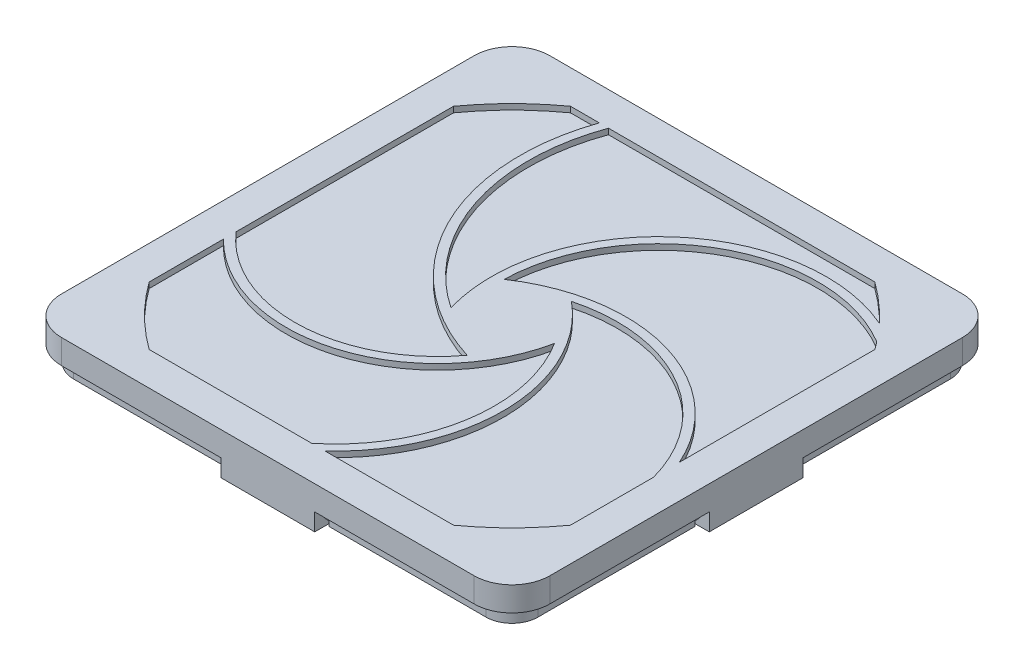
SolidWorks part; units mm, degrees
material "Custom Plastic"
ref_plane "Front" through (0, 0, 0) normal (0, 0, 1) x (1, 0, 0)
ref_plane "Top" through (0, 0, 0) normal (0, 1, 0) x (1, 0, 0)
ref_plane "Right" through (0, 0, 0) normal (1, 0, 0) x (0, 0, -1)
sketch "Sketch2" plane through (0, 0, 0) normal (0, 1, 0) x (1, 0, 0)
  line L1 (-52.4, 62) -> (52.4, 62)
  line L2 (-62, 52.4) -> (-62, -52.4)
  line L3 (-52.4, -62) -> (52.4, -62)
  line L4 (62, 52.4) -> (62, -52.4)
  line L5 (-52.4, 52.4) -> (52.4, 52.4) construction
  line L6 (-52.4, 52.4) -> (-52.4, -52.4) construction
  line L7 (-52.4, -52.4) -> (52.4, -52.4) construction
  line L8 (52.4, 52.4) -> (52.4, -52.4) construction
  arc A0 (-62, -52.4) -> (-52.4, -62) centre (-52.4, -52.4) ccw
  arc A1 (52.4, -62) -> (62, -52.4) centre (52.4, -52.4) ccw
  arc A2 (62, 52.4) -> (52.4, 62) centre (52.4, 52.4) ccw
  arc A3 (-62, 52.4) -> (-52.4, 62) centre (-52.4, 52.4) cw
  circle A4 centre (-52.4, 52.4) radius 2.25 construction
  circle A5 centre (52.4, 52.4) radius 2.25 construction
  circle A6 centre (-52.4, -52.4) radius 2.25 construction
  circle A7 centre (52.4, -52.4) radius 2.25 construction
  point P12 (0, 62)
  point P13 (-62, 0)
  dimension "D2" = 4.5
  dimension "D1" = 124
  dimension "D3" = 104.8
extrude "Boss-Extrude1" add sketch "Sketch2" along normal blind 6.2
ref_plane "Plane1" through (0, 3.1, 0) normal (0, 1, 0) x (-1, 0, 0)
sketch "Sketch11" plane through (0, 0, 0) normal (0, -1, 0) x (1, 0, 0)
  line L8 (-59.4, 52.4) -> (-59.4, -52.4)
  line L9 (-52.4, -59.4) -> (52.4, -59.4)
  line L10 (59.4, -52.4) -> (59.4, 52.4)
  line L11 (52.4, 59.4) -> (-52.4, 59.4)
  line L12 (-59.4, 52.4) -> (-59.4, -52.4)
  line L13 (-52.4, -59.4) -> (52.4, -59.4)
  line L14 (59.4, -52.4) -> (59.4, 52.4)
  line L15 (52.4, 59.4) -> (-52.4, 59.4)
  arc A8 (-52.4, 59.4) -> (-59.4, 52.4) centre (-52.4, 52.4) ccw
  arc A9 (-59.4, -52.4) -> (-52.4, -59.4) centre (-52.4, -52.4) ccw
  arc A10 (52.4, -59.4) -> (59.4, -52.4) centre (52.4, -52.4) ccw
  arc A11 (59.4, 52.4) -> (52.4, 59.4) centre (52.4, 52.4) ccw
  arc A12 (-52.4, 59.4) -> (-59.4, 52.4) centre (-52.4, 52.4) ccw
  arc A13 (-59.4, -52.4) -> (-52.4, -59.4) centre (-52.4, -52.4) ccw
  arc A14 (52.4, -59.4) -> (59.4, -52.4) centre (52.4, -52.4) ccw
  arc A15 (59.4, 52.4) -> (52.4, 59.4) centre (52.4, 52.4) ccw
  dimension "D1" = 2.6
extrude "Cut-Extrude5" cut sketch "Sketch11" against normal offset from surface (4.5 mm away) 1.7 up to face at (0, 6.2, 0)
sketch "Sketch13" plane through (0, 4.5, 0) normal (0, -1, 0) x (1, 0, 0)
  line L8 (-59, 52.4) -> (-59, -52.4)
  line L9 (-52.4, -59) -> (52.4, -59)
  line L10 (59, -52.4) -> (59, 52.4)
  line L11 (52.4, 59) -> (-52.4, 59)
  arc A0 (52.4, -59) -> (59, -52.4) centre (52.4, -52.4) ccw
  circle A1 centre (-52.4, 52.4) radius 2.25 construction
  circle A2 centre (52.4, 52.4) radius 2.25 construction
  circle A3 centre (-52.4, -52.4) radius 2.25 construction
  circle A4 centre (52.4, -52.4) radius 2.25 construction
  circle A5 centre (-52.4, 52.4) radius 2.25
  circle A6 centre (52.4, 52.4) radius 2.25
  circle A7 centre (-52.4, -52.4) radius 2.25
  arc A8 (59, 52.4) -> (52.4, 59) centre (52.4, 52.4) ccw
  arc A9 (-59, 52.4) -> (-52.4, 59) centre (-52.4, 52.4) cw
  arc A10 (-52.4, -59) -> (-59, -52.4) centre (-52.4, -52.4) cw
  circle A12 centre (52.4, -52.4) radius 2.25
  point P3 (-59, 0)
  point P8 (0, 59)
  dimension "D1" = 118
extrude "Boss-Extrude7" add sketch "Sketch13" along normal blind 6.9 from offset 2 separate body
sketch "Sketch17" plane through (0, -4.4, 0) normal (0, -1, 0) x (1, 0, 0)
  line L9 (56, -52.4) -> (56, 52.4)
  line L10 (52.4, 56) -> (-52.4, 56)
  line L11 (-56, 52.4) -> (-56, -52.4)
  line L12 (-52.4, -56) -> (52.4, -56)
  line L13 (56, -47.9164) -> (56, 47.9164)
  line L14 (47.9164, 56) -> (-47.9164, 56)
  line L15 (-56, 47.9164) -> (-56, -47.9164)
  line L16 (-47.9164, -56) -> (47.9164, -56)
  arc A9 (52.4, -56) -> (56, -52.4) centre (52.4, -52.4) ccw
  arc A10 (56, 52.4) -> (52.4, 56) centre (52.4, 52.4) ccw
  arc A11 (-52.4, 56) -> (-56, 52.4) centre (-52.4, 52.4) ccw
  arc A12 (-56, -52.4) -> (-52.4, -56) centre (-52.4, -52.4) ccw
  arc A17 (47.9164, 56) -> (56, 47.9164) centre (52.4, 52.4) ccw
  circle A18 centre (-52.4, 52.4) radius 5.75
  arc A19 (-56, 47.9164) -> (-47.9164, 56) centre (-52.4, 52.4) ccw
  arc A20 (-47.9164, -56) -> (-56, -47.9164) centre (-52.4, -52.4) ccw
  arc A21 (56, -47.9164) -> (47.9164, -56) centre (52.4, -52.4) ccw
  dimension "D2" = 3.5
  dimension "D1" = 3
extrude "Cut-Extrude8" cut sketch "Sketch17" against normal offset from surface (4.88 mm away) 2.02 up to face at (-52.4, 2.5, -54.65)
sketch "Sketch12" plane through (0, 0, 0) normal (0, 0, 1) x (1, 0, 0)
  line L1 (62, -4.4) -> (57.75, -4.4)
  line L2 (57.75, -4.4) -> (59.4, -2.75)
  line L3 (59.4, -2.75) -> (59.4, 0)
  line L4 (59.4, 0) -> (62, 0)
  line L5 (62, -4.4) -> (62, 0)
  dimension "D1" = 10.6
  dimension "D2" = 45
  dimension "D3" = 4.25
extrude "Boss-Extrude6" add sketch "Sketch12" along normal mid plane 23.8
ref_axis "Axis1" through (0, 6.73, 0) along (0, -1, 0)
pattern_circular "CirPattern3" count 4 over 360 about axis through (0, 0, 0) along (0, 1, 0) of "Boss-Extrude6"
sketch "Sketch14" plane through (0, 0, 0) normal (0, 0, 1) x (1, 0, 0)
  line L5 (59.4, 0) -> (59.4, -2.75) construction
  line L6 (62.25, -4.65) -> (62.25, 0.25)
  line L7 (62.25, -4.65) -> (62.25, 0.25)
  line L11 (57.1464, -4.65) -> (62.25, -4.65)
  line L12 (59.15, -2.6464) -> (57.1464, -4.65)
  line L13 (59.15, 0.25) -> (59.15, -2.6464)
  line L14 (62.25, 0.25) -> (59.15, 0.25)
  line L16 (57.1464, -4.65) -> (62.25, -4.65)
  line L17 (59.4, -2.3964) -> (57.1464, -4.65)
  line L18 (59.4, 0.25) -> (59.4, -2.3964)
  line L19 (62.25, 0.25) -> (59.4, 0.25)
  dimension "D1" = 0.25
extrude "Cut-Extrude6" cut sketch "Sketch14" against normal mid plane 25
pattern_circular "CirPattern4" count 4 over 360 about axis through (0, 0, 0) along (0, 1, 0) of "Cut-Extrude6"
sketch "Sketch3" plane through (0, 6.2, 0) normal (0, 1, 0) x (1, 0, 0)
  line L1 (-62, 52.4) -> (-62, -52.4) construction
  line L2 (52.4, 62) -> (-52.4, 62) construction
  line L3 (-52.4, -62) -> (52.4, -62) construction
  line L4 (62, -52.4) -> (62, 52.4) construction
  line L9 (-52.4, -53.5) -> (52.4, -53.5)
  line L14 (53.5, -52.4) -> (53.5, 52.4)
  line L15 (52.4, 53.5) -> (-52.4, 53.5)
  line L16 (-53.5, 52.4) -> (-53.5, -52.4)
  line L17 (-38.6491, -53.5) -> (38.6491, -53.5)
  line L18 (53.5, -38.6491) -> (53.5, 38.6491)
  line L19 (38.6491, 53.5) -> (-38.6491, 53.5)
  line L20 (-53.5, 38.6491) -> (-53.5, -38.6491)
  arc A6 (-38.6491, 53.5) -> (-53.5, 38.6491) centre (0, 0) ccw
  arc A7 (-9.5, -6) -> (-29, 53.5) centre (18.7657, 36.2089) cw
  arc A8 (3, -14.3909) -> (-53.5, -16.5603) centre (-26.1196, 7.1728) cw
  arc A9 (11.5, -0.7) -> (-53.5, -19.8) centre (-26.1196, 7.1728) cw
  arc A10 (9.3466, -0.2494) -> (-51.9327, -18.2561) centre (-26.1196, 7.1728) cw construction
  arc A11 (11.5, -0.7) -> (2.6256, -53.5) centre (-22.7116, -22.0956) cw
  arc A12 (53.5, 38.6491) -> (38.6491, 53.5) centre (0, 0) ccw
  arc A13 (38.6491, -53.5) -> (53.5, -38.6491) centre (0, 0) ccw
  arc A14 (-53.5, -38.6491) -> (-38.6491, -53.5) centre (0, 0) ccw
  arc A15 (-9.5, -6) -> (48.2804, 45) centre (31.3459, 5.9548) cw
  arc A16 (-53.5, -52.4) -> (-52.4, -53.5) centre (-52.4, -52.4) ccw
  arc A17 (52.4, -53.5) -> (53.5, -52.4) centre (52.4, -52.4) ccw
  arc A18 (53.5, 52.4) -> (52.4, 53.5) centre (52.4, 52.4) ccw
  arc A19 (-52.4, 53.5) -> (-53.5, 52.4) centre (-52.4, 52.4) ccw
  arc A20 (-27.179, 18.0074) -> (4.5155, -51.8763) centre (-22.7116, -22.0956) cw construction
  arc A21 (-27.4226, 20.1939) -> (6, -53.5) centre (-22.7116, -22.0956) cw construction
  arc A22 (-13.981, 3.0712) -> (53.5, -11) centre (14.7098, -28.1813) cw construction
  arc A23 (-9, 7) -> (53.5, -11) centre (14.7098, -28.1813) cw
  arc A24 (4.4, 10.7) -> (53.5, -17.5339) centre (14.7098, -28.1813) cw
  arc A25 (4.4, 10.7) -> (6, -53.5) centre (-22.7116, -22.0956) cw
  arc A26 (-12.4932, 1.4505) -> (51.4885, -11.891) centre (14.7098, -28.1813) cw construction
  arc A27 (-9, 7) -> (52.0233, 40.615) centre (31.3459, 5.9548) cw
  arc A28 (-7.3886, -5.382) -> (47.405, 42.9817) centre (31.3459, 5.9548) cw construction
  arc A31 (3, -14.3909) -> (-31.3334, 53.5) centre (18.7657, 36.2089) cw
  point P2 (8.8597, 25.9395)
  point P10 (-15.7592, 44.8536)
  point P11 (-2.9616, -2.7675)
  dimension "D1" = 132
  dimension "D2" = 8.5
  dimension "D3" = 61.3
  dimension "D4" = 52.5
  dimension "D5" = 73.5
  dimension "D13" = 51
  dimension "D22" = 47.6091
  dimension "D7" = 68
  dimension "D10" = 42.2
  dimension "D14" = 56
  dimension "D18" = 2.2
  dimension "D19" = 57.6
  dimension "D12" = 2.2
  dimension "D8" = 33
  dimension "D9" = 17
  dimension "D11" = 2.2
  dimension "D15" = 71
  dimension "D16" = 2.2
  dimension "D17" = 55
  dimension "D20" = 51.3
  dimension "D21" = 65
  dimension "D6" = 2.2
extrude "Cut-Extrude4" cut sketch "Sketch3" against normal through all contours A7 A15 A12 L19 | A8 A31 L19 A6 L20 | A27 A23 L18 A12 | A24 A25 L17 A13 L18 | L20 A14 L17 A11 A9
sketch "Sketch18" plane through (0, 4.5, 0) normal (0, -1, 0) x (1, 0, 0)
  line L0 (-57.9, 47.9) -> (-47.9, 57.9)
  line L1 (-47.9, 57.9) -> (47.9, 57.9)
  line L2 (-57.9, 47.9) -> (-57.9, -47.9)
  line L3 (-47.9, -57.9) -> (47.9, -57.9)
  line L4 (57.9, 47.9) -> (57.9, -47.9)
  line L5 (47.9, 57.9) -> (57.9, 47.9)
  line L6 (57.9, -47.9) -> (47.9, -57.9)
  line L7 (-47.9, -57.9) -> (-57.9, -47.9)
  point P0 (0, 57.9)
  point P2 (-57.9, 0)
  dimension "D1" = 45
  dimension "D2" = 10
  dimension "D3" = 115.8
extrude "Boss-Extrude8" add sketch "Sketch18" along normal blind 3.3 from offset 0.25 separate body offset against normal yes
sketch "Sketch20" plane through (0, 0, 0) normal (1, 0, 0) x (0, 0, -1)
  line L0 (10.7, 2.5) -> (-53.5, 2.5) construction
  line L1 (-59, 2.5) -> (-56.7, 2.5)
  line L2 (-59, 2.5) -> (-59, 0.48)
  line L3 (-59, 0.48) -> (-56.7, 0.48)
  line L4 (-56.7, 2.5) -> (-56.7, 0.48)
  line L5 (-40.74, 2.5) -> (-35.06, 2.5) construction
  line L6 (-56.7, 2.5) -> (-51.02, 2.5) construction
  line L7 (-51.02, 2.5) -> (-48.72, 2.5)
  line L8 (-51.02, 2.5) -> (-51.02, 0.48)
  line L9 (-51.02, 0.48) -> (-48.72, 0.48)
  line L10 (-48.72, 2.5) -> (-48.72, 0.48)
  line L11 (-19.1, 2.5) -> (-16.8, 2.5)
  line L12 (-19.1, 2.5) -> (-19.1, 0.48)
  line L13 (-19.1, 0.48) -> (-16.8, 0.48)
  line L14 (-16.8, 2.5) -> (-16.8, 0.48)
  line L15 (-48.72, 2.5) -> (-43.04, 2.5) construction
  line L18 (-24.78, 2.5) -> (-19.1, 2.5) construction
  line L19 (-35.06, 2.5) -> (-32.76, 2.5)
  line L20 (-43.04, 2.5) -> (-40.74, 2.5)
  line L21 (-27.08, 2.5) -> (-24.78, 2.5)
  line L22 (-27.08, 2.5) -> (-27.08, 0.48)
  line L23 (-27.08, 0.48) -> (-24.78, 0.48)
  line L24 (-24.78, 2.5) -> (-24.78, 0.48)
  line L25 (-43.04, 2.5) -> (-43.04, 0.48)
  line L26 (-43.04, 0.48) -> (-40.74, 0.48)
  line L27 (-40.74, 2.5) -> (-40.74, 0.48)
  line L28 (-35.06, 2.5) -> (-35.06, 0.48)
  line L29 (-35.06, 0.48) -> (-32.76, 0.48)
  line L30 (-32.76, 2.5) -> (-32.76, 0.48)
  line L31 (-32.76, 2.5) -> (-27.08, 2.5) construction
  line L32 (-53.5, 0.48) -> (10.7, 0.48) construction
  dimension "D1" = 2.3
  dimension "D2" = 16.8
  dimension "D3" = 59
revolve "Revolve1" add sketch "Sketch20" angle 360 mid plane about axis through (0, 6.73, 0) along (0, -1, 0)
sketch "Sketch10" plane through (0, 0, 0) normal (0, 1, 0) x (1, 0, 0)
  line L0 (-59.5, 59.5) -> (59.5, -59.5) construction
  line L1 (-59.5, 59.5) -> (59.5, 59.5)
  line L2 (-59.5, 59.5) -> (-59.5, -59.5)
  line L3 (-59.5, -59.5) -> (59.5, -59.5)
  line L4 (59.5, 59.5) -> (59.5, -59.5)
  dimension "D1" = 119
chamfer "Chamfer1" distance 2 angle 45 4 edges at (-52.4, 2.5, -54.65) (52.4, 2.5, -54.65) (-52.4, 2.5, 50.15) (52.4, 2.5, 50.15)
delete or keep bodies "Plastic" [suppressed] type delete bodies bodies 144 156
